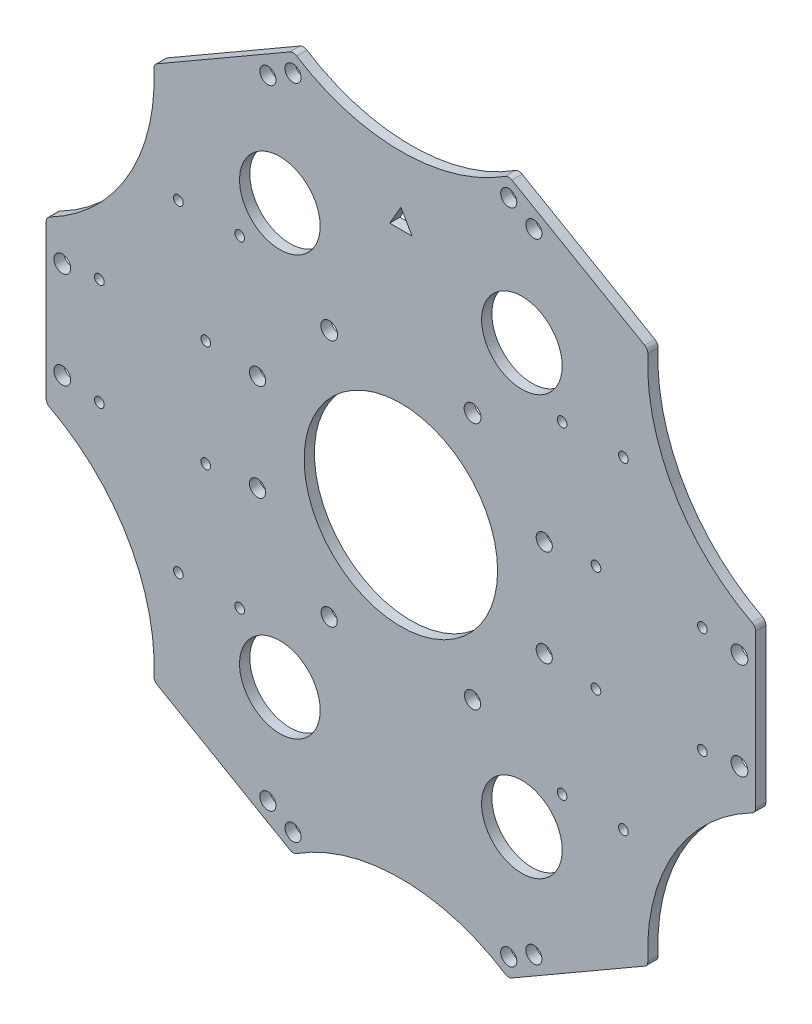
SolidWorks part; units mm, degrees
ref_plane "Front Plane" through (0, 0, 0) normal (0, 0, 1) x (1, 0, 0)
ref_plane "Top Plane" through (0, 0, 0) normal (0, 1, 0) x (1, 0, 0)
ref_plane "Right Plane" through (0, 0, 0) normal (1, 0, 0) x (0, 0, -1)
sketch "Sketch1" plane through (0, 0, 0) normal (0, 0, 1) x (1, 0, 0)
  line L0 (-65, -95.2628) -> (-62.5, -90.9327) construction
  line L1 (-10, 127.0171) -> (-120, 63.5085) construction
  line L2 (-120, 63.5085) -> (-120, -63.5085) construction
  line L3 (-120, -63.5085) -> (-10, -127.0171) construction
  line L4 (-10, -127.0171) -> (100, -63.5085) construction
  line L5 (100, -63.5085) -> (100, 63.5085) construction
  line L6 (100, 63.5085) -> (-10, 127.0171) construction
  line L7 (-54.456, 0) -> (-32.228, -38.5) construction
  line L8 (-32.228, -38.5) -> (12.228, -38.5) construction
  line L9 (12.228, -38.5) -> (34.456, 0) construction
  line L10 (34.456, 0) -> (12.228, 38.5) construction
  line L11 (12.228, 38.5) -> (-32.228, 38.5) construction
  line L12 (-32.228, 38.5) -> (-54.456, 0) construction
  line L13 (-120, 0) -> (-115, 0) construction
  line L14 (-115, -15) -> (-115, 15) construction
  line L15 (100, 0) -> (95, 0) construction
  line L16 (-65, 95.2628) -> (-62.5, 90.9327) construction
  line L17 (45, 95.2628) -> (42.5, 90.9327) construction
  line L18 (45, -95.2628) -> (42.5, -90.9327) construction
  line L19 (95, -15) -> (95, 15) construction
  line L20 (-62.5, -90.9327) -> (-51.2417, -97.4327) construction
  line L21 (42.5, -90.9327) -> (31.2417, -97.4327) construction
  line L22 (-62.5, 90.9327) -> (-51.2417, 97.4327) construction
  line L23 (42.5, 90.9327) -> (31.2417, 97.4327) construction
  line L24 (-51.2417, -97.4327) -> (-43.4474, -101.9327) construction
  line L25 (31.2417, -97.4327) -> (23.4474, -101.9327) construction
  line L26 (-51.2417, 97.4327) -> (-43.4474, 101.9327) construction
  line L27 (31.2417, 97.4327) -> (23.4474, 101.9327) construction
  line L28 (-120, -25) -> (-120, 25)
  line L29 (100, -25) -> (100, 25)
  line L30 (66.6506, 82.7628) -> (23.3494, 107.7628)
  line L31 (-86.6506, 82.7628) -> (-43.3494, 107.7628)
  line L32 (-86.6506, -82.7628) -> (-43.3494, -107.7628)
  line L33 (23.3494, -107.7628) -> (66.6506, -82.7628)
  line L34 (-54.456, 15) -> (-54.456, -15) construction
  line L35 (34.456, 15) -> (34.456, -15) construction
  line L36 (-10, 0) -> (0, 0) construction
  line L37 (-60, -50) -> (-60, 50) construction
  line L38 (40, -50) -> (40, 50) construction
  line L39 (-60, 0) -> (40, 0) construction
  line L40 (-60, 0) -> (-79, 0) construction
  line L41 (40, 0) -> (59, 0) construction
  line L42 (-79, -50) -> (-79, 50) construction
  line L43 (59, -50) -> (59, 50) construction
  line L44 (-115, 0) -> (-54.456, 0) construction
  line L45 (34.456, 0) -> (95, 0) construction
  line L47 (65.0555, 0) -> (27.5278, 65) construction
  line L48 (27.5278, 65) -> (-47.5278, 65) construction
  line L49 (-10, 97.6408) -> (-10, 82.6408) construction
  line L50 (-10, 82.6408) -> (-13.4641, 76.6408)
  line L51 (-13.4641, 76.6408) -> (-6.5359, 76.6408)
  line L52 (-6.5359, 76.6408) -> (-10, 82.6408)
  line L53 (-47.5278, 65) -> (-85.0555, 0) construction
  line L54 (-85.0555, 0) -> (-47.5278, -65) construction
  line L55 (-47.5278, -65) -> (27.5278, -65) construction
  line L56 (27.5278, -65) -> (65.0555, 0) construction
  circle A0 centre (-10, 0) radius 110 construction
  circle A1 centre (-10, 0) radius 35 construction
  circle A2 centre (12.228, -38.5) radius 2.5
  circle A3 centre (-54.456, 15) radius 2.5
  circle A4 centre (12.228, 38.5) radius 2.6
  circle A5 centre (-32.228, 38.5) radius 2.6
  circle A6 centre (-54.456, -15) radius 2.5
  circle A7 centre (-32.228, -38.5) radius 2.5
  circle A8 centre (95, 15) radius 2.6
  circle A9 centre (95, -15) radius 2.6
  circle A10 centre (-115, -15) radius 2.6
  circle A11 centre (-115, 15) radius 2.6
  circle A12 centre (31.2417, -97.4327) radius 2.5
  circle A13 centre (23.4474, -101.9327) radius 2.5
  circle A14 centre (-43.4474, -101.9327) radius 2.5
  circle A15 centre (-51.2417, -97.4327) radius 2.5
  circle A16 centre (-51.2417, 97.4327) radius 2.5
  circle A17 centre (-43.4474, 101.9327) radius 2.5
  circle A18 centre (23.4474, 101.9327) radius 2.5
  circle A19 centre (31.2417, 97.4327) radius 2.5
  arc A20 (-120, 25) -> (-86.6506, 82.7628) centre (-146.521, 78.8204) ccw
  arc A21 (-86.6506, -82.7628) -> (-120, -25) centre (-146.521, -78.8204) ccw
  arc A22 (66.6506, 82.7628) -> (100, 25) centre (126.521, 78.8204) ccw
  arc A23 (100, -25) -> (66.6506, -82.7628) centre (126.521, -78.8204) ccw
  arc A24 (23.3494, -107.7628) -> (-43.3494, -107.7628) centre (-10, -157.6408) ccw
  arc A25 (-43.3494, 107.7628) -> (23.3494, 107.7628) centre (-10, 157.6408) ccw
  circle A26 centre (34.456, -15) radius 2.5
  circle A27 centre (34.456, 15) radius 2.5
  circle A28 centre (-79, 50) radius 1.5
  circle A29 centre (-60, 50) radius 1.5
  circle A30 centre (-60, -50) radius 1.5
  circle A31 centre (-79, -50) radius 1.5
  circle A32 centre (40, -50) radius 1.5
  circle A33 centre (59, -50) radius 1.5
  circle A34 centre (59, 50) radius 1.5
  circle A35 centre (40, 50) radius 1.5
  circle A36 centre (-10, 0) radius 65 construction
  circle A39 centre (27.5278, -65) radius 12.5
  circle A40 centre (-10, 78.6408) radius 2 construction
  circle A41 centre (-10, 0) radius 30
  circle A42 centre (-47.5278, -65) radius 12.5
  circle A43 centre (-47.5278, 65) radius 12.5
  circle A44 centre (27.5278, 65) radius 12.5
  point P38 (95, 0)
  point P39 (-115, 0)
  point P72 (-65, 95.2628)
  point P73 (-120, 0)
  point P74 (-65, -95.2628)
  point P75 (45, -95.2628)
  point P76 (100, 0)
  point P77 (45, 95.2628)
  point P78 (-54.456, 0)
  point P84 (34.456, 0)
  point P99 (40, 0)
  point P100 (-10, 0)
  point P107 (59, 0)
  point P108 (-79, 0)
  dimension "D1" = 220
  dimension "D2" = 70
  dimension "D4" = 5
  dimension "D10" = 120
  dimension "D16" = 130
  dimension "D20" = 4
  dimension "D21" = 60
  dimension "D15" = 3
  dimension "D17" = 25
  dimension "D3" = 5
  dimension "D5" = 30
  dimension "D6" = 13
  dimension "D7" = 9
  dimension "D8" = 127.0171
  dimension "D9" = 50
  dimension "D11" = 10
  dimension "D12" = 100
  dimension "D13" = 100
  dimension "D14" = 19
  dimension "D19" = 15
extrude "Boss-Extrude1" add sketch "Sketch1" along normal blind 3.175
fillet "Fillet1" radius 2 12 edges at (-86.6506, -82.7628, 1.5875) (-43.3494, -107.7628, 1.5875) (23.3494, -107.7628, 1.5875) (66.6506, -82.7628, 1.5875) (-43.3494, 107.7628, 1.5875) (66.6506, 82.7628, 1.5875) (100, -25, 1.5875) (100, 25, 1.5875) (23.3494, 107.7628, 1.5875) (-86.6506, 82.7628, 1.5875) (-120, -25, 1.5875) (-120, 25, 1.5875)
sketch "Sketch3" plane through (0, 0, 3.175) normal (0, 0, 1) x (1, 0, 0)
  line L0 (-87, 0) -> (-120, 0) construction
  line L2 (100, -23.77) -> (100, 23.77) construction
  line L3 (-10, 0) -> (-10, -97.6408) construction
  line L4 (-103.5, 16.5) -> (-70.5, -16.5) construction
  line L5 (50.5, 16.5) -> (83.5, 16.5) construction
  line L6 (50.5, 16.5) -> (50.5, -16.5) construction
  line L7 (50.5, -16.5) -> (83.5, -16.5) construction
  line L8 (83.5, 16.5) -> (83.5, -16.5) construction
  line L9 (-103.5, 16.5) -> (-70.5, 16.5) construction
  line L10 (-103.5, 16.5) -> (-103.5, -16.5) construction
  line L11 (-103.5, -16.5) -> (-70.5, -16.5) construction
  line L12 (-70.5, 16.5) -> (-70.5, -16.5) construction
  line L13 (50.5, 16.5) -> (83.5, -16.5) construction
  line L14 (67, 0) -> (100, 0) construction
  line L15 (-120, 0) -> (-10, 0) construction
  line L16 (-120, 23.77) -> (-120, -23.77) construction
  arc A0 (22.3367, -107.1004) -> (-42.3367, -107.1004) centre (-10, -157.6408) ccw construction
  circle A1 centre (-103.5, 16.5) radius 1.5
  circle A2 centre (-70.5, 16.5) radius 1.5
  circle A3 centre (-70.5, -16.5) radius 1.5
  circle A4 centre (-103.5, -16.5) radius 1.5
  circle A5 centre (50.5, -16.5) radius 1.5
  circle A6 centre (83.5, -16.5) radius 1.5
  circle A7 centre (50.5, 16.5) radius 1.5
  circle A8 centre (83.5, 16.5) radius 1.5
  dimension "D4" = 3
  dimension "D1" = 33
  dimension "D2" = 33
  dimension "D3" = 110
extrude "Cut-Extrude1" cut sketch "Sketch3" against normal blind 4
